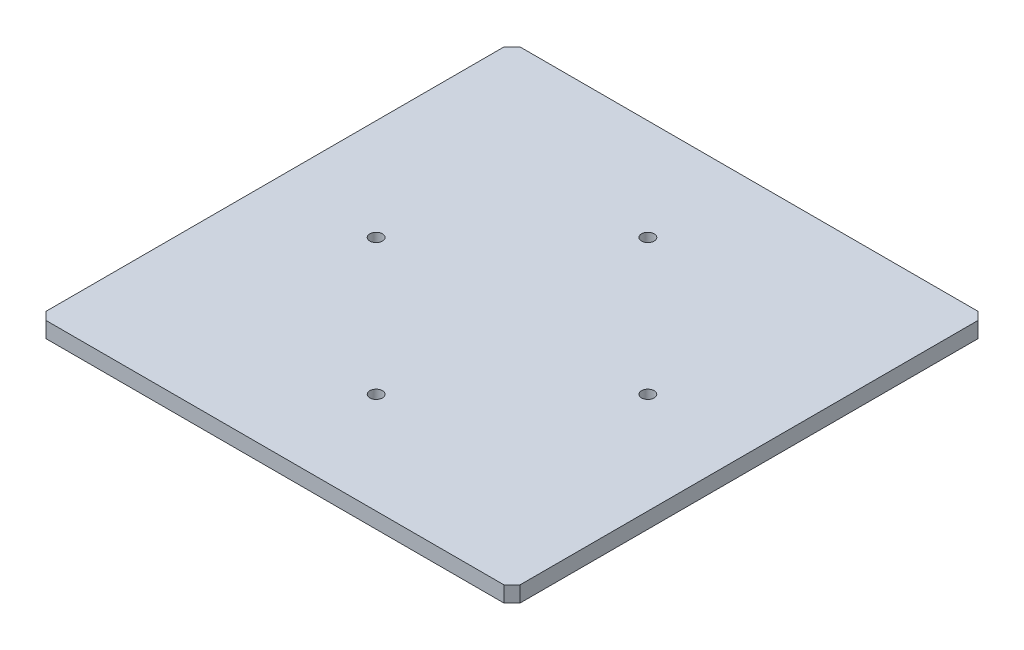
SolidWorks part; units mm, degrees
ref_plane "정면도" through (0, 0, 0) normal (0, 0, 1) x (1, 0, 0)
ref_plane "평면도" through (0, 0, 0) normal (0, 1, 0) x (1, 0, 0)
ref_plane "우측면도" through (0, 0, 0) normal (1, 0, 0) x (0, 0, -1)
sketch "스케치1" plane through (0, 0, 0) normal (0, 1, 0) x (1, 0, 0)
  line L1 (-150, -150) -> (150, -150)
  line L2 (-150, -150) -> (-150, 150)
  line L3 (-150, 150) -> (150, 150)
  line L4 (150, -150) -> (150, 150)
  line L5 (0, 150) -> (0, -150) construction
  line L6 (-150, 0) -> (150, 0) construction
  point P0 (0, 0)
  dimension "D1" = 300
  dimension "D2" = 300
extrude "보스-돌출1" add sketch "스케치1" along normal blind 10
chamfer "모따기1" distance 5 4 edges at (-150, 5, -150) (150, 5, -150) (-150, 5, 150) (150, 5, 150)
sketch "스케치2" plane through (0, 10, 0) normal (0, 1, 0) x (1, 0, 0)
  circle A0 centre (0, 0) radius 86 construction
  circle A1 centre (0, -86) radius 4
  circle A2 centre (-86, 0) radius 4
  circle A3 centre (0, 86) radius 4
  circle A4 centre (86, 0) radius 4
  point P5 (48.7288, 6.0397)
  point P6 (0, 0)
  point P14 (0, 0)
  dimension "D1" = 172
  dimension "D2" = 8
  dimension "D3" = 4
extrude "컷-돌출1" cut sketch "스케치2" against normal blind 10
